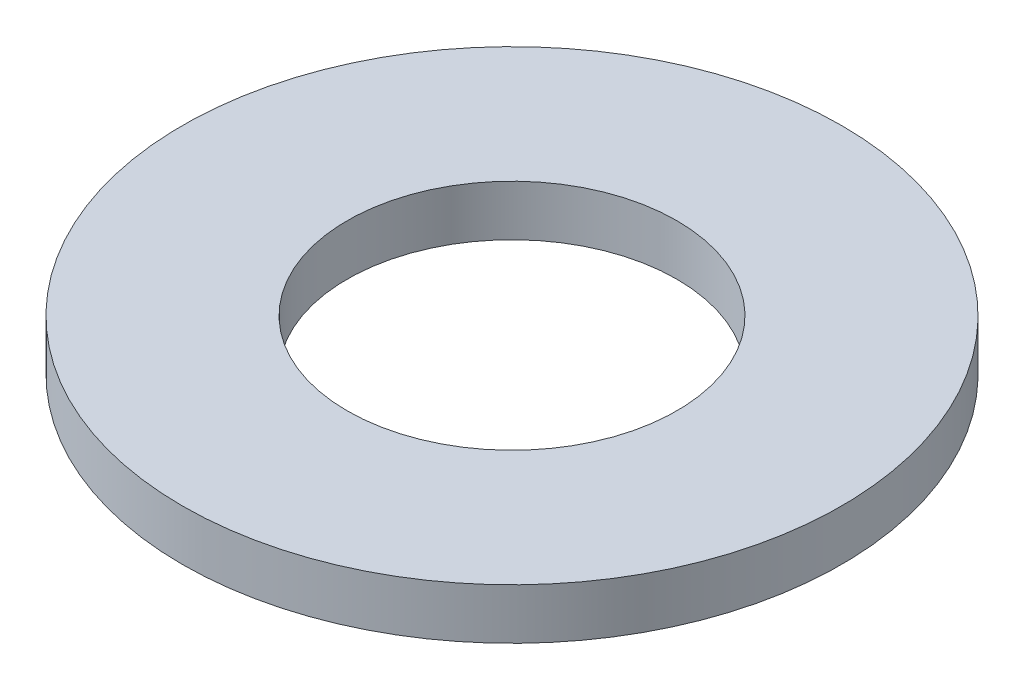
SolidWorks part; units mm, degrees
ref_plane "Front Plane" through (0, 0, 0) normal (0, 0, 1) x (1, 0, 0)
ref_plane "Top Plane" through (0, 0, 0) normal (0, 1, 0) x (1, 0, 0)
ref_plane "Right Plane" through (0, 0, 0) normal (1, 0, 0) x (0, 0, -1)
sketch "Sketch1" plane through (0, 0, 0) normal (0, 1, 0) x (1, 0, 0)
  circle A0 centre (0, 0) radius 5.1594
  circle A1 centre (0, 0) radius 10.3187
  dimension "D1" = 10.3187
  dimension "D2" = 20.6375
extrude "Boss-Extrude1" add sketch "Sketch1" along normal blind 1.5875
